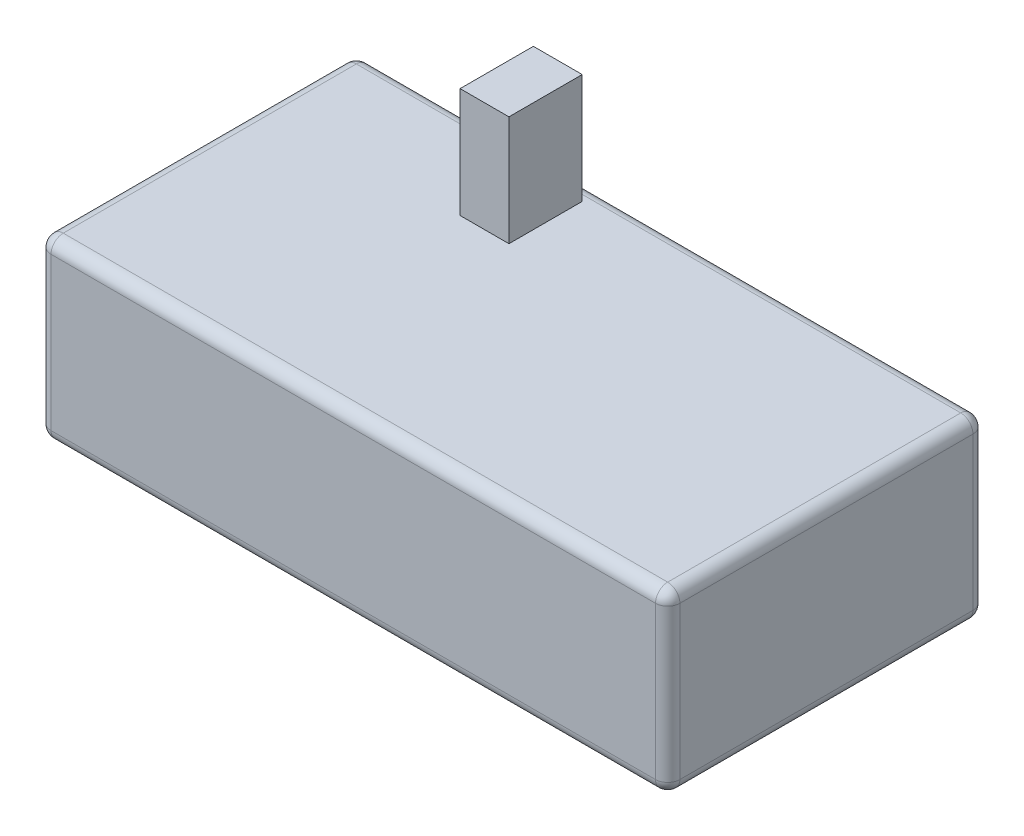
SolidWorks part; units mm, degrees
ref_plane "Front Plane" through (0, 0, 0) normal (0, 0, 1) x (1, 0, 0)
ref_plane "Top Plane" through (0, 0, 0) normal (0, 1, 0) x (1, 0, 0)
ref_plane "Right Plane" through (0, 0, 0) normal (1, 0, 0) x (0, 0, -1)
sketch "Sketch1" plane through (0, 0, 0) normal (0, 1, 0) x (1, 0, 0)
  line L0 (65.405, -33.02) -> (-65.405, 33.02) construction
  line L1 (-65.405, 33.02) -> (65.405, 33.02)
  line L2 (-65.405, 33.02) -> (-65.405, -33.02)
  line L3 (-65.405, -33.02) -> (65.405, -33.02)
  line L4 (65.405, 33.02) -> (65.405, -33.02)
  dimension "D1" = 66.04
  dimension "D2" = 130.81
extrude "Boss-Extrude1" add sketch "Sketch1" along normal blind 36.83
fillet "Fillet1" radius 2.54 12 edges at (0, 0, -33.02) (-65.405, 18.415, -33.02) (-65.405, 0, 0) (-65.405, 18.415, 33.02) (0, 0, 33.02) (65.405, 18.415, 33.02) (65.405, 18.415, -33.02) (65.405, 0, 0) (0, 36.83, -33.02) (65.405, 36.83, 0) (0, 36.83, 33.02) (-65.405, 36.83, 0)
sketch "Sketch2" plane through (0, 36.83, 0) normal (0, 1, 0) x (1, 0, 0)
  line L0 (-65.405, 13.97) -> (-14.605, 13.97) construction
  line L1 (-65.405, -30.48) -> (-65.405, 30.48) construction
  line L2 (-62.865, 33.02) -> (62.865, 33.02) construction
  line L4 (-14.605, 13.97) -> (-24.765, 13.97)
  line L5 (-14.605, 13.97) -> (-14.605, 29.21)
  line L6 (-14.605, 29.21) -> (-24.765, 29.21)
  line L7 (-24.765, 13.97) -> (-24.765, 29.21)
  dimension "D1" = 40.64
  dimension "D2" = 19.05
  dimension "D3" = 15.24
  dimension "D4" = 10.16
extrude "Boss-Extrude2" add sketch "Sketch2" along normal blind 22.86
sketch "Sketch3" plane through (0, 0, -33.02) normal (0, 0, -1) x (-1, 0, 0)
  line L0 (-0.595, 0) -> (-0.595, 12) construction
  line L1 (62.865, 0) -> (-62.865, 0) construction
  line L2 (65.405, 34.29) -> (65.405, 2.54) construction
  line L4 (-0.595, 12) -> (12.405, 12)
  line L5 (-0.595, 12) -> (-0.595, 7.936)
  line L6 (-0.595, 7.936) -> (12.405, 7.936)
  line L7 (12.405, 12) -> (12.405, 7.936)
  dimension "D1" = 12
  dimension "D2" = 66
  dimension "D3" = 13
  dimension "D4" = 4.064
extrude "Boss-Extrude3" add sketch "Sketch3" along normal blind 9.525
sketch "Sketch4" plane through (0, 12, 0) normal (0, 1, 0) x (1, 0, 0)
  line L0 (0.595, 40.513) -> (-12.405, 40.513) construction
  line L1 (0.595, 42.545) -> (0.595, 33.02) construction
  line L2 (-12.405, 42.545) -> (-12.405, 33.02) construction
  line L3 (-12.405, 42.545) -> (0.595, 42.545) construction
  line L4 (-8.341, 33.02) -> (-8.341, 42.545) construction
  line L5 (-12.405, 33.02) -> (0.595, 33.02) construction
  line L6 (-3.469, 33.02) -> (-3.469, 42.545) construction
  line L7 (-3.469, 35.433) -> (-8.341, 35.433)
  line L8 (-3.469, 40.513) -> (-8.341, 40.513)
  line L9 (-8.341, 40.513) -> (-8.341, 35.433)
  line L10 (-3.469, 35.433) -> (-3.469, 40.513)
  dimension "D1" = 2.032
  dimension "D2" = 4.064
  dimension "D3" = 4.064
  dimension "D4" = 5.08
extrude "Cut-Extrude1" cut sketch "Sketch4" against normal through all
